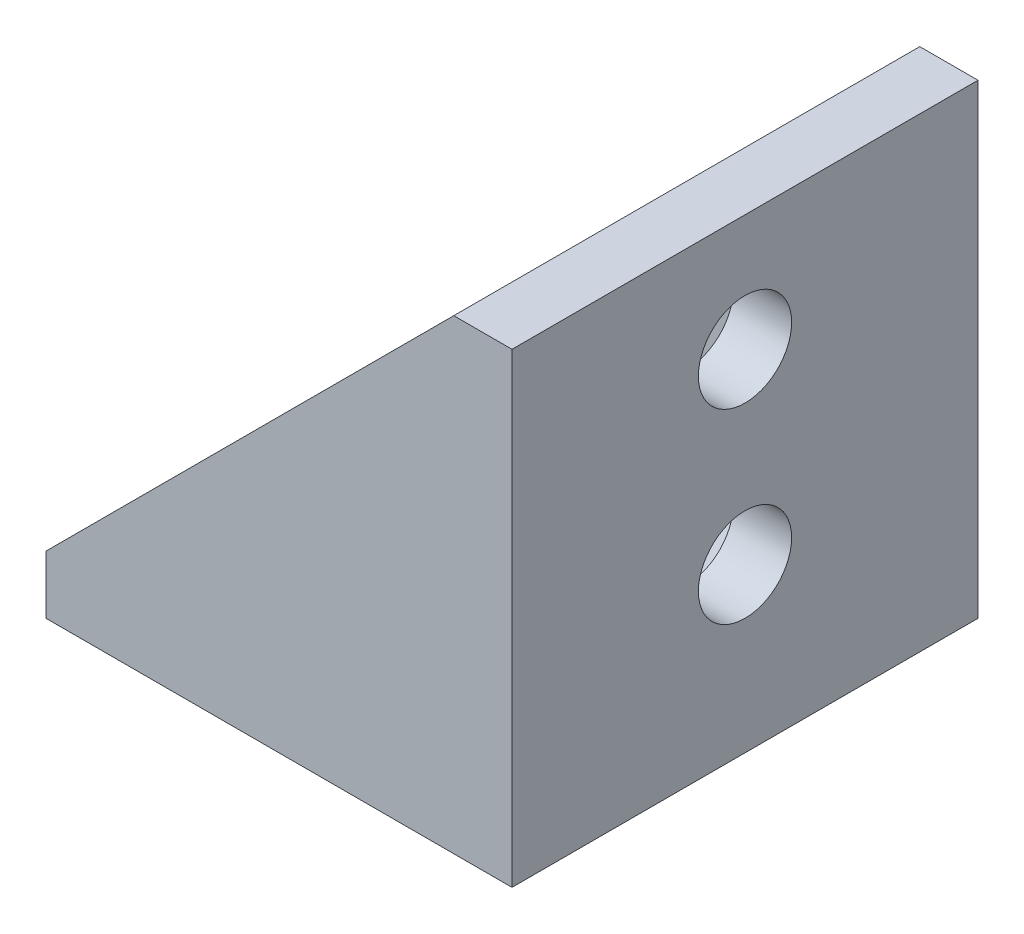
SolidWorks part; units mm, degrees
material "聚脂树脂"
ref_plane "前视基准面" through (0, 0, 0) normal (0, 0, 1) x (1, 0, 0)
ref_plane "上视基准面" through (0, 0, 0) normal (0, 1, 0) x (1, 0, 0)
ref_plane "右视基准面" through (0, 0, 0) normal (1, 0, 0) x (0, 0, -1)
other "Configuration Table"
sketch "草图1" plane through (0, 0, 0) normal (0, 0, 1) x (1, 0, 0)
  line L0 (0, 0) -> (20, 0)
  line L1 (20, 0) -> (20, 20)
  line L2 (20, 20) -> (17.5, 20)
  line L3 (17.5, 20) -> (0, 2.5)
  line L4 (0, 2.5) -> (0, 0)
  dimension "D1" = 20
  dimension "D2" = 2.5
extrude "凸台-拉伸1" add sketch "草图1" against normal blind 20
sketch "草图2" plane through (0, 0, 0) normal (0, 1, 0) x (1, 0, 0)
  line L0 (17.5, 20) -> (17.5, 0) construction
  line L1 (17.5, 18.3) -> (0, 18.3)
  line L2 (17.5, 18.3) -> (17.5, 1.7)
  line L3 (17.5, 1.7) -> (0, 1.7)
  line L4 (0, 18.3) -> (0, 1.7)
  line L5 (0, 20) -> (0, 0) construction
  line L6 (17.5, 0) -> (0, 0) construction
  line L7 (17.5, 20) -> (0, 20) construction
  dimension "D1" = 1.7
  dimension "D2" = 1.7
extrude "切除-拉伸1" cut sketch "草图2" against normal blind 17.5 from surface at 20 starting at face at (18.75, 20, -10)
sketch "草图3" plane through (0, 0, 0) normal (0, 1, 0) x (1, 0, 0)
  line L0 (0, 1.7) -> (0, 18.3) construction
  line L1 (-5.4427, 9.954) -> (23.4572, 9.954) construction
  circle A0 centre (5, 9.954) radius 2
  circle A1 centre (13, 9.954) radius 2
  dimension "D1" = 4
  dimension "D2" = 5
  dimension "D3" = 8
extrude "切除-拉伸2" cut sketch "草图3" along normal up to next
sketch "草图4" plane through (0, 0, 0) normal (1, 0, 0) x (0, 0, -1)
  line L0 (10, -3.7714) -> (10, 26.0587) construction
  line L1 (20, 20) -> (0, 20) construction
  circle A0 centre (10, 15) radius 2
  circle A1 centre (10, 7) radius 2
  point P6 (0, 0)
  point P7 (0, 0)
  dimension "D4" = 4
  dimension "D1" = 10
  dimension "D2" = 5
  dimension "D3" = 8
extrude "切除-拉伸3" cut sketch "草图4" along normal up to next
